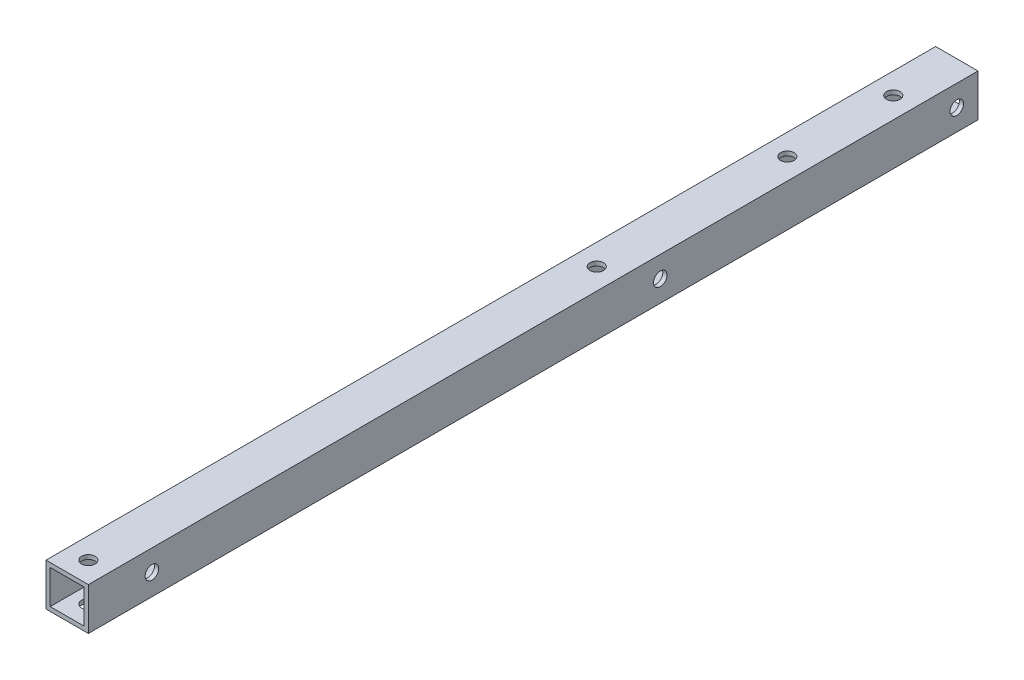
SolidWorks part; units mm, degrees
ref_plane "正面" through (0, 0, 0) normal (0, 0, 1) x (1, 0, 0)
ref_plane "平面" through (0, 0, 0) normal (0, 1, 0) x (1, 0, 0)
ref_plane "右側面" through (0, 0, 0) normal (1, 0, 0) x (0, 0, -1)
sketch "ｽｹｯﾁ1" plane through (0, 0, 0) normal (0, 0, 1) x (1, 0, 0)
  line L0 (-4, 4) -> (-4, -4)
  line L1 (-5, 5) -> (5, 5)
  line L2 (-5, 5) -> (-5, -5)
  line L3 (-5, -5) -> (5, -5)
  line L4 (5, 5) -> (5, -5)
  line L5 (-5, 5) -> (5, -5) construction
  line L6 (-5, -5) -> (5, 5) construction
  line L7 (-4, -4) -> (4, -4)
  line L8 (4, 4) -> (4, -4)
  line L9 (-4, 4) -> (4, 4)
  point P0 (0, 0)
  dimension "D1" = 10
  dimension "D2" = 10
  dimension "D3" = 1
extrude "ﾎﾞｽ - 押し出し1" add sketch "ｽｹｯﾁ1" along normal blind 210
sketch "ｽｹｯﾁ2" plane through (-5, 0, 0) normal (-1, 0, 0) x (0, 0, 1)
  line L0 (5.5, 0) -> (-5.5, 0) construction
  line L1 (0, -5.5) -> (0, 5.5) construction
  circle A0 centre (5, 0) radius 1.6
  circle A1 centre (75, 0) radius 1.6
  circle A2 centre (195, 0) radius 1.6
  dimension "D1" = 3.2
  dimension "D2" = 3.2
  dimension "D3" = 5
  dimension "D4" = 70
  dimension "D5" = 3.2
  dimension "D6" = 195
extrude "ｶｯﾄ - 押し出し1" cut sketch "ｽｹｯﾁ2" against normal through all
sketch "ｽｹｯﾁ3" plane through (0, 5, 0) normal (0, 1, 0) x (1, 0, 0)
  line L0 (0, -5.5) -> (0, 5.5) construction
  line L1 (-5.5, 0) -> (5.5, 0) construction
  circle A0 centre (0, -15) radius 1.6
  circle A1 centre (0, -85) radius 1.6
  circle A2 centre (0, -40) radius 1.6
  dimension "D1" = 3.2
  dimension "D2" = 3.2
  dimension "D3" = 70
  dimension "D4" = 15
  dimension "D5" = 3.2
  dimension "D6" = 40
extrude "ｶｯﾄ - 押し出し2" cut sketch "ｽｹｯﾁ3" against normal through all
sketch "ｽｹｯﾁ4" plane through (0, 5, 0) normal (0, 1, 0) x (1, 0, 0)
  line L0 (0, -5.5) -> (0, 5.5) construction
  line L1 (-5.5, 0) -> (5.5, 0) construction
  circle A0 centre (0, -205) radius 1.6
  dimension "D1" = 3.2
  dimension "D2" = 205
extrude "ｶｯﾄ - 押し出し3" cut sketch "ｽｹｯﾁ4" against normal through all
